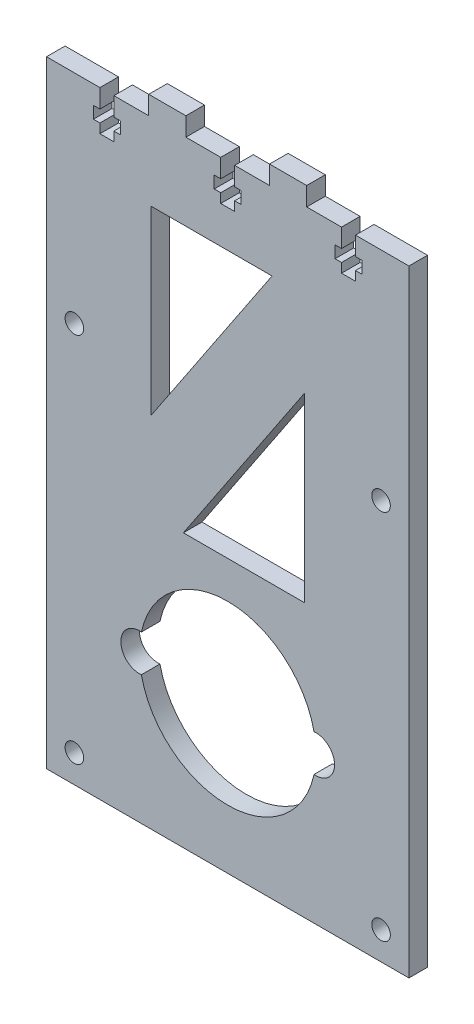
SolidWorks part; units mm, degrees
ref_plane "前视基准面" through (0, 0, 0) normal (0, 0, 1) x (1, 0, 0)
ref_plane "上视基准面" through (0, 0, 0) normal (0, 1, 0) x (1, 0, 0)
ref_plane "右视基准面" through (0, 0, 0) normal (1, 0, 0) x (0, 0, -1)
sketch "草图1" plane through (0, 0, 0) normal (0, 0, 1) x (1, 0, 0)
  line L0 (-1.5, 0) -> (1.5, 0) construction
  line L1 (1.5, 0) -> (1.5, -4)
  line L2 (1.5, -4) -> (2.9, -4)
  line L3 (2.9, -4) -> (2.9, -6.6)
  line L4 (2.9, -6.6) -> (1.5, -6.6)
  line L5 (1.5, -6.6) -> (1.5, -8.6)
  line L6 (1.5, -8.6) -> (-1.5, -8.6)
  line L7 (0, 0) -> (0, -2.7531) construction
  line L8 (-1.5, -6.6) -> (-1.5, -8.6)
  line L9 (-2.9, -6.6) -> (-1.5, -6.6)
  line L10 (-2.9, -4) -> (-2.9, -6.6)
  line L11 (-1.5, -4) -> (-2.9, -4)
  line L12 (-1.5, 0) -> (-1.5, -4)
  line L13 (1.5, 0) -> (9, 0)
  line L14 (9, 0) -> (9, 4)
  line L15 (9, 4) -> (17, 4)
  line L16 (17, 4) -> (17, 0)
  line L17 (13, 4) -> (13, 2.1555) construction
  line L18 (27.5, -4) -> (28.9, -4)
  line L19 (28.9, -6.6) -> (27.5, -6.6)
  line L20 (23.1, -6.6) -> (24.5, -6.6)
  line L21 (24.5, -4) -> (23.1, -4)
  line L22 (23.1, -4) -> (23.1, -6.6)
  line L23 (28.9, -4) -> (28.9, -6.6)
  line L24 (27.5, -6.6) -> (27.5, -8.6)
  line L25 (24.5, -6.6) -> (24.5, -8.6)
  line L26 (24.5, -8.6) -> (27.5, -8.6)
  line L27 (24.5, 0) -> (24.5, -4)
  line L28 (27.5, 0) -> (27.5, -4)
  line L29 (17, 0) -> (24.5, 0)
  line L30 (27.5, 0) -> (39, 0)
  line L31 (39, 0) -> (39, -132.7127)
  line L32 (39, -132.7127) -> (-39, -132.7127)
  line L33 (-13, 4) -> (-13, 2.1555) construction
  line L34 (-17, 0) -> (-24.5, 0)
  line L35 (-27.5, 0) -> (-27.5, -4)
  line L36 (-24.5, 0) -> (-24.5, -4)
  line L37 (-24.5, -8.6) -> (-27.5, -8.6)
  line L38 (-24.5, -6.6) -> (-24.5, -8.6)
  line L39 (-27.5, -6.6) -> (-27.5, -8.6)
  line L40 (-28.9, -4) -> (-28.9, -6.6)
  line L41 (-23.1, -4) -> (-23.1, -6.6)
  line L42 (-24.5, -4) -> (-23.1, -4)
  line L43 (-23.1, -6.6) -> (-24.5, -6.6)
  line L44 (-28.9, -6.6) -> (-27.5, -6.6)
  line L45 (-27.5, -4) -> (-28.9, -4)
  line L46 (-17, 4) -> (-17, 0)
  line L47 (-9, 4) -> (-17, 4)
  line L48 (-9, 0) -> (-9, 4)
  line L49 (-9, 0) -> (-1.5, 0)
  line L50 (-27.5, 0) -> (-39, 0)
  line L51 (-39, 0) -> (-39, -132.7127)
  line L52 (0, 0) -> (0, -101) construction
  circle A0 centre (0, -101) radius 19 construction
  circle A1 centre (-19, -101) radius 4 construction
  circle A2 centre (19, -101) radius 4 construction
  arc A3 (18.5789, -97.0222) -> (-18.5789, -97.0222) centre (0, -101) ccw
  arc A4 (-18.5789, -104.9778) -> (18.5789, -104.9778) centre (0, -101) ccw
  arc A5 (-18.5789, -104.9778) -> (-18.5789, -97.0222) centre (-19, -101) cw
  arc A6 (18.5789, -104.9778) -> (18.5789, -97.0222) centre (19, -101) ccw
  point P12 (0, -8.6)
  point P75 (-39, -125.3185)
  dimension "D9" = 78
  dimension "D1" = 4
  dimension "D2" = 1.5
  dimension "D3" = 2.6
  dimension "D4" = 2
  dimension "D5" = 2.9
  dimension "D6" = 7.5
  dimension "D7" = 4
  dimension "D8" = 8
extrude "凸台-拉伸1" add sketch "草图1" along normal blind 4
sketch "草图2" plane through (0, 0, 0) normal (0, 1, 0) x (1, 0, 0)
  line L0 (-1.5, -2) -> (1.5, -2)
  line L1 (-1.5, -4) -> (-1.5, 0) construction
  line L2 (1.5, -4) -> (1.5, 0) construction
  circle A0 centre (0, -2) radius 1.5
sketch "草图3" plane through (0, 0, 0) normal (0, 0, -1) x (-1, 0, 0)
  line L0 (39, -132.7127) -> (-39, -132.7127) construction
  line L1 (39, 0) -> (39, -132.7127) construction
  circle A0 centre (33, -126.7127) radius 2
  circle A1 centre (33, -46.7127) radius 2
  circle A2 centre (-33, -46.7127) radius 2
  circle A3 centre (-33, -126.7127) radius 2
  dimension "D1" = 6
  dimension "D2" = 6
  dimension "D3" = 2
  dimension "D4" = 2
extrude "切除-拉伸1" cut sketch "草图3" against normal blind 10
sketch "草图4" plane through (0, 0, 0) normal (0, 0, -1) x (-1, 0, 0)
  line L0 (24.5, -8.6) -> (24.5, -82) construction
  line L1 (24.5, -82) -> (-24.5, -8.6) construction
  line L2 (-24.5, -8.6) -> (24.5, -8.6) construction
  line L3 (16.5, -16.6) -> (16.5, -55.6077)
  line L4 (16.5, -55.6077) -> (-9.5406, -16.6)
  line L5 (-9.5406, -16.6) -> (16.5, -16.6)
  line L6 (24.5, -82) -> (-24.5, -82) construction
  line L7 (-24.5, -82) -> (-24.5, -8.6) construction
  line L8 (9.5406, -74) -> (-16.5, -34.9923)
  line L9 (-16.5, -74) -> (-16.5, -34.9923)
  line L10 (9.5406, -74) -> (-16.5, -74)
  point P12 (0, 0)
  point P13 (24.5, -8.6)
  dimension "D1" = 8
  dimension "D2" = 8
extrude "切除-拉伸2" cut sketch "草图4" against normal blind 10
